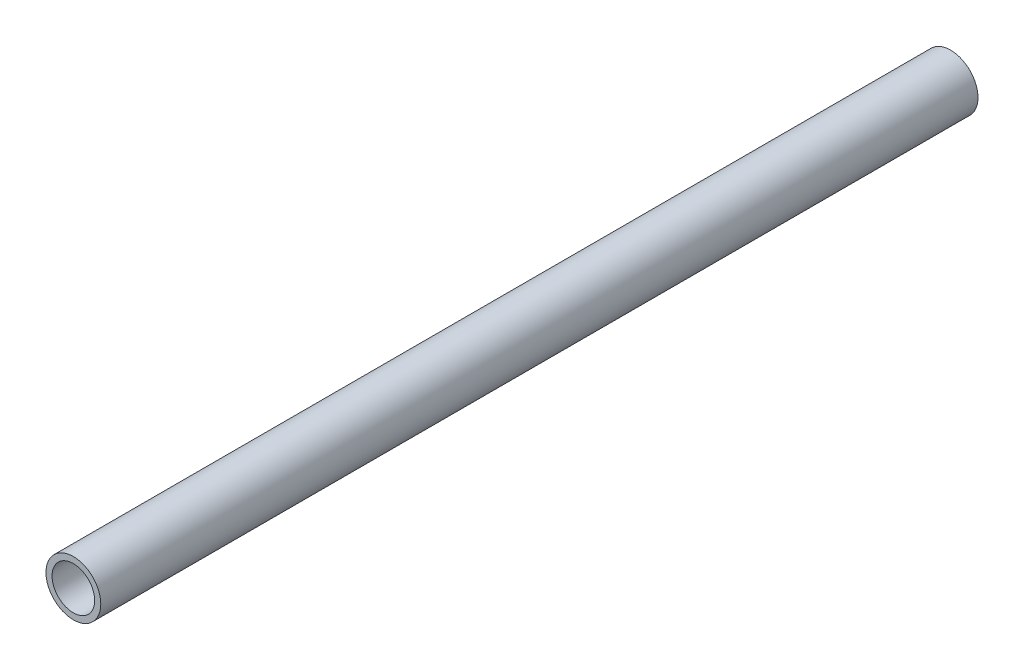
SolidWorks part; units mm, degrees
material "201 Annealed Stainless Steel (SS)"
ref_plane "Front Plane" through (0, 0, 0) normal (0, 0, 1) x (1, 0, 0)
ref_plane "Top Plane" through (0, 0, 0) normal (0, 1, 0) x (1, 0, 0)
ref_plane "Right Plane" through (0, 0, 0) normal (1, 0, 0) x (0, 0, -1)
sketch "Sketch1" plane through (0, 0, 0) normal (0, 0, 1) x (1, 0, 0)
  circle A0 centre (0, 0) radius 28.575
  circle A1 centre (0, 0) radius 22.225
  dimension "D1" = 57.15
  dimension "D2" = 44.45
extrude "Boss-Extrude1" add sketch "Sketch1" along normal blind 914.4
sketch "Sketch2" plane through (0, 0, 0) normal (0, 1, 0) x (1, 0, 0)
  line L0 (22.225, 0) -> (-22.225, 0) construction
  line L1 (28.575, -914.4) -> (28.575, 0) construction
  line L2 (-28.575, -914.4) -> (28.575, -914.4) construction
  circle A0 centre (-3.175, -38.1) radius 4.7625
  circle A1 centre (-0.0062, -88.8011) radius 4.7625
  circle A2 centre (0, -876.3) radius 4.7625
  circle A3 centre (0, -825.5) radius 4.7625
  dimension "D1" = 9.525
  dimension "D2" = 9.525
  dimension "D3" = 9.525
  dimension "D4" = 9.525
  dimension "D5" = 38.1
  dimension "D6" = 50.8
  dimension "D7" = 31.75
  dimension "D8" = 38.1
  dimension "D9" = 50.8
extrude "Cut-Extrude1" cut sketch "Sketch2" against normal through all
